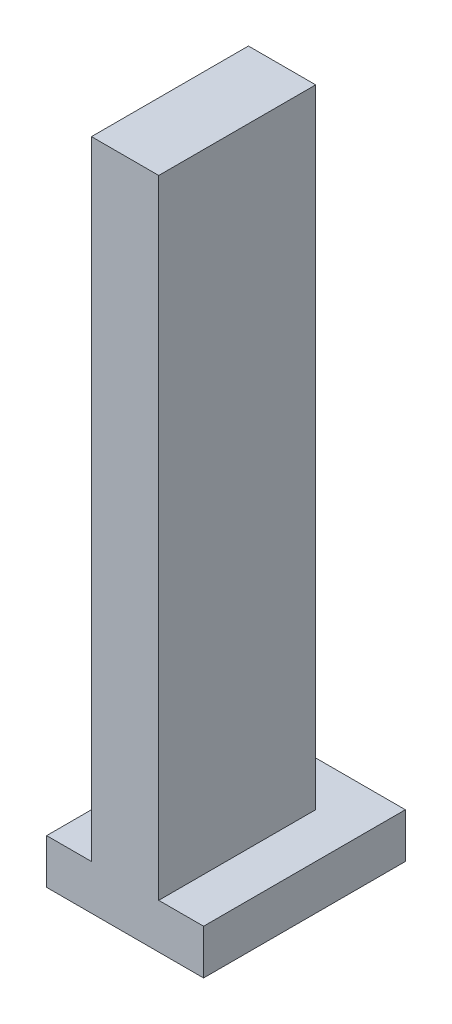
SolidWorks part; units mm, degrees
ref_plane "Front Plane" through (0, 0, 0) normal (0, 0, 1) x (1, 0, 0)
ref_plane "Top Plane" through (0, 0, 0) normal (0, 1, 0) x (1, 0, 0)
ref_plane "Right Plane" through (0, 0, 0) normal (1, 0, 0) x (0, 0, -1)
sketch "Sketch1" plane through (0, 0, 0) normal (0, 1, 0) x (1, 0, 0)
  line L1 (-0.75, 1.75) -> (0.75, 1.75)
  line L2 (-0.75, 1.75) -> (-0.75, -1.75)
  line L3 (-0.75, -1.75) -> (0.75, -1.75)
  line L4 (0.75, 1.75) -> (0.75, -1.75)
  line L5 (-0.75, 1.75) -> (0.75, -1.75) construction
  line L6 (-0.75, -1.75) -> (0.75, 1.75) construction
  point P0 (0, 0)
  dimension "D1" = 1.5
  dimension "D2" = 3.5
extrude "Boss-Extrude1" add sketch "Sketch1" along normal blind 15
sketch "Sketch2" plane through (0, 0, 0) normal (0, 1, 0) x (1, 0, 0)
  line L1 (-1.75, 2.75) -> (1.75, 2.75)
  line L2 (-1.75, 2.75) -> (-1.75, -2.75)
  line L3 (-1.75, -2.75) -> (1.75, -2.75)
  line L4 (1.75, 2.75) -> (1.75, -2.75)
  line L5 (-1.75, 2.75) -> (1.75, -2.75) construction
  line L6 (-1.75, -2.75) -> (1.75, 2.75) construction
  point P0 (0, 0)
  dimension "D1" = 5.5
  dimension "D2" = 3.5
extrude "Boss-Extrude2" add sketch "Sketch2" along normal blind 1
sketch "Sketch3" plane through (0, 1, 0) normal (0, 1, 0) x (1, 0, 0)
  line L0 (-1.75, 2.75) -> (-1.75, -2.75) construction
  line L1 (1.75, -2.75) -> (-1.75, -2.75)
  line L2 (1.75, -2.75) -> (1.75, -1.75)
  line L3 (1.75, -1.75) -> (-1.75, -1.75)
  line L4 (-1.75, -2.75) -> (-1.75, -1.75)
  line L5 (-0.75, -1.75) -> (0.75, -1.75) construction
extrude "Cut-Extrude1" cut sketch "Sketch3" against normal blind 1
